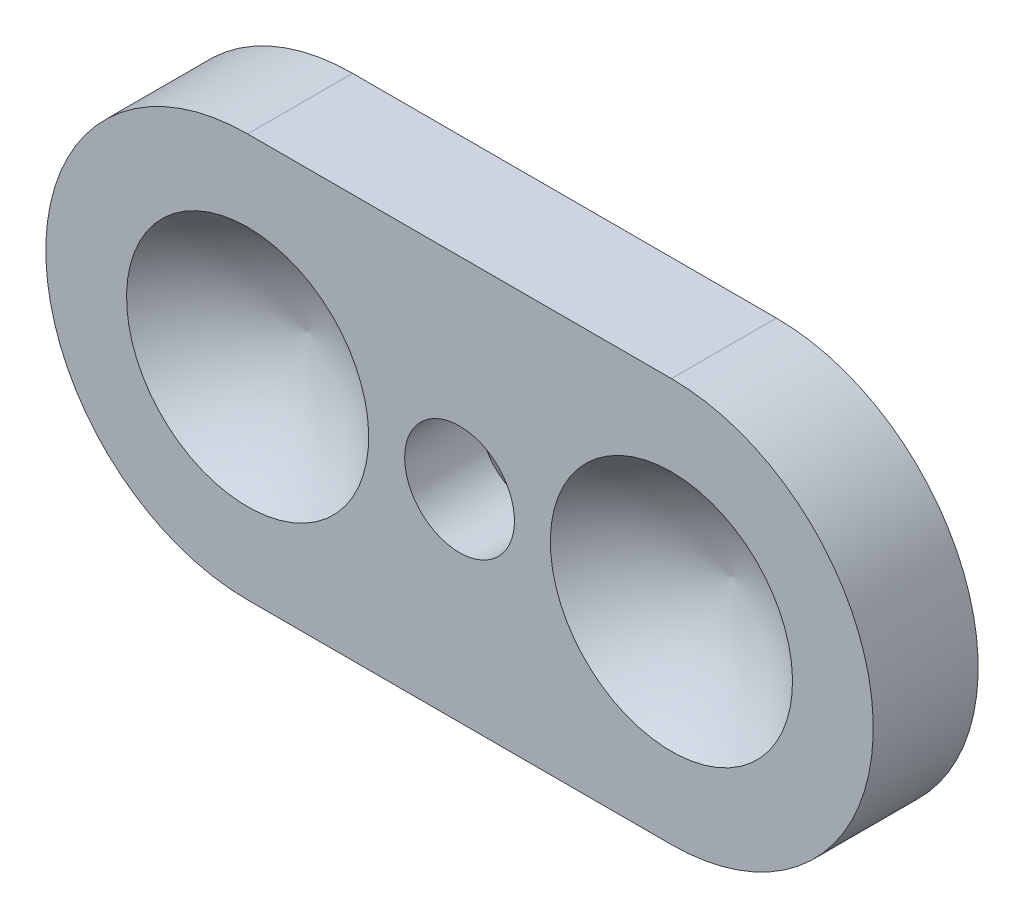
SolidWorks part; units mm, degrees
material "Plain Carbon Steel"
ref_plane "Front Plane" through (0, 0, 0) normal (0, 0, 1) x (1, 0, 0)
ref_plane "Top Plane" through (0, 0, 0) normal (0, 1, 0) x (1, 0, 0)
ref_plane "Right Plane" through (0, 0, 0) normal (1, 0, 0) x (0, 0, -1)
sketch "Sketch1" plane through (0, 0, 0) normal (0, 0, 1) x (1, 0, 0)
  line L1 (-6.6675, 6.35) -> (6.6675, 6.35)
  line L3 (-6.6675, -6.35) -> (6.6675, -6.35)
  arc A0 (-6.6675, 6.35) -> (-6.6675, -6.35) centre (-6.6675, 0) ccw
  arc A3 (6.6675, -6.35) -> (6.6675, 6.35) centre (6.6675, 0) ccw
  point P1 (0, 6.35)
  dimension "D1" = 12.7
extrude "Boss-Extrude1" add sketch "Sketch1" along normal blind 3.302
sketch "Sketch2" plane through (0, 0, 3.302) normal (0, 0, 1) x (1, 0, 0)
  circle A0 centre (-6.6675, 0) radius 3.81
  circle A1 centre (6.6675, 0) radius 3.81
  dimension "D1" = 7.62
ref_plane "Plane1" through (6.6675, 0, 0) normal (1, 0, 0) x (0, 0, -1)
sketch "Sketch4" plane through (6.6675, 0, 0) normal (1, 0, 0) x (0, 0, -1)
  line L1 (-3.302, 3.81) -> (-3.302, 0)
  line L3 (-1.397, 0) -> (-3.302, 0)
  arc A0 (-3.302, 3.81) -> (-1.397, 0) centre (-8.0268, -0.9336) cw
  dimension "D1" = 1.905
revolve "Cut-Revolve3" cut sketch "Sketch4" angle 360 about L3
mirror "Mirror1" about plane through (0, 0, 0) normal (1, 0, 0) of "Cut-Revolve3"
hole_wizard "CSK for #4 Flat Head Machine Screw (100)1" positions "Sketch7" profile "Sketch8" countersink size "#4" standard "ANSI Inch" end condition through all
sketch "Sketch7" plane through (0, 0, 0) normal (0, 0, -1) x (-1, 0, 0)
  point P0 (0, 0)
sketch "Sketch8" plane through (0, 0, 0) normal (1, 0, 0) x (0, 1, 0)
  line L0 (0, 0) -> (0, 3.302)
  line L1 (0, 3.302) -> (1.7272, 3.302)
  line L2 (1.7272, 3.302) -> (1.7272, 0.9484)
  line L3 (1.7272, 0.9484) -> (2.8575, 0)
  line L5 (2.8575, 0) -> (0, 0)
  line L6 (-1.7272, 0.9484) -> (-2.8575, 0) construction
  line L11 (0, -6.35) -> (0, 107.95) construction
  dimension "Thru Hole Dia." = 3.4544
  dimension "Thru Hole Depth" = 3.302
  dimension "Near C'Sink Dia." = 5.715
  dimension "Near C'Sink Angle" = 100
